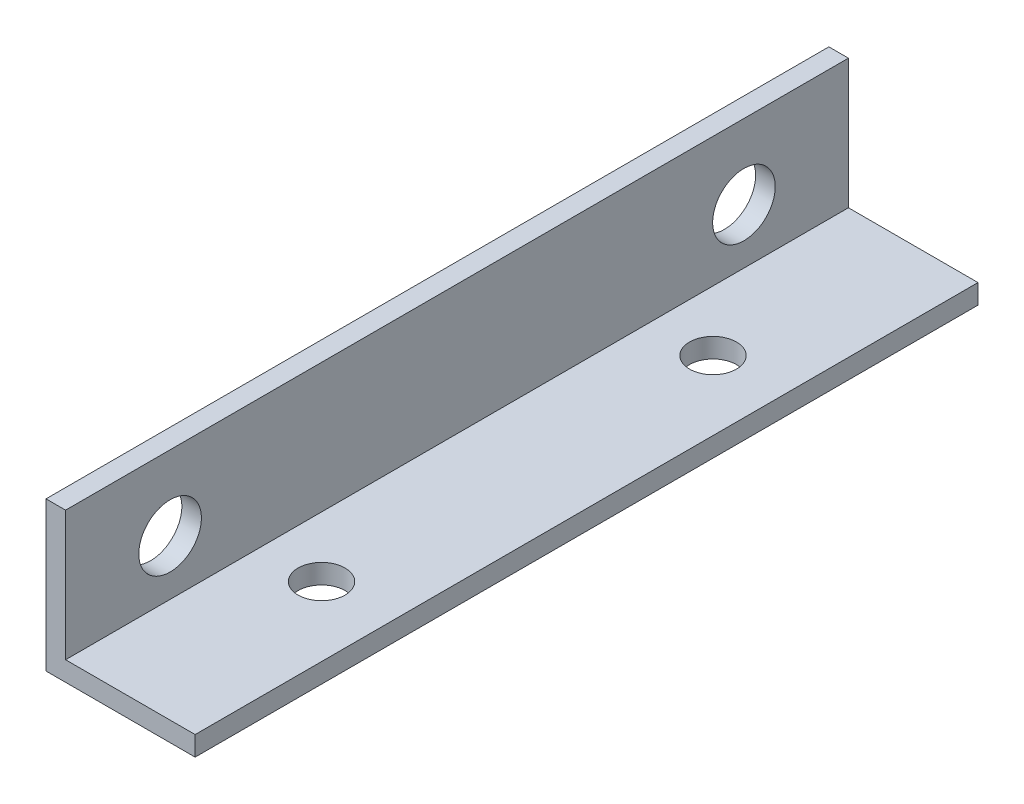
SolidWorks part; units mm, degrees
material "6061-T4 (SS)"
ref_plane "Front Plane" through (0, 0, 0) normal (0, 0, 1) x (1, 0, 0)
ref_plane "Top Plane" through (0, 0, 0) normal (0, 1, 0) x (1, 0, 0)
ref_plane "Right Plane" through (0, 0, 0) normal (1, 0, 0) x (0, 0, -1)
sketch "Sketch1" plane through (0, 0, 0) normal (0, 0, 1) x (1, 0, 0)
  line L0 (0, 0) -> (0, 19.05)
  line L2 (19.05, 0) -> (0, 0)
  dimension "D1" = 19.05
  dimension "D2" = 19.05
extrude "Extrude-Thin1" add sketch "Sketch1" along normal mid plane 100 thin
sketch "Sketch4" plane through (0, 0, 0) normal (-1, 0, 0) x (0, 0, 1)
  line L0 (0, 0) -> (0, 19.05) construction
  line L1 (50, 19.05) -> (-50, 19.05) construction
  line L2 (-36.65, 9.525) -> (36.65, 9.525) construction
  circle A0 centre (-36.65, 9.525) radius 4
  circle A1 centre (36.65, 9.525) radius 4
  point P9 (0, 9.525)
  dimension "D1" = 73.3
  dimension "D2" = 8
extrude "Cut-Extrude2" cut sketch "Sketch4" against normal up to next
sketch "Sketch5" plane through (0, 0, 0) normal (0, -1, 0) x (1, 0, 0)
  line L0 (10.2, 50) -> (10.2, -50) construction
  line L2 (19.05, -50) -> (0, -50) construction
  line L3 (19.05, 50) -> (0, 50) construction
  line L4 (0, 0) -> (19.05, 0) construction
  line L5 (19.05, 50) -> (19.05, -50) construction
  line L6 (0, 50) -> (0, -50) construction
  circle A0 centre (10.2, 25) radius 3
  circle A1 centre (10.2, -25) radius 3
  point P15 (0, 0)
  dimension "D2" = 6
  dimension "D1" = 25
  dimension "D3" = 10.2
extrude "Cut-Extrude3" cut sketch "Sketch5" against normal through all
